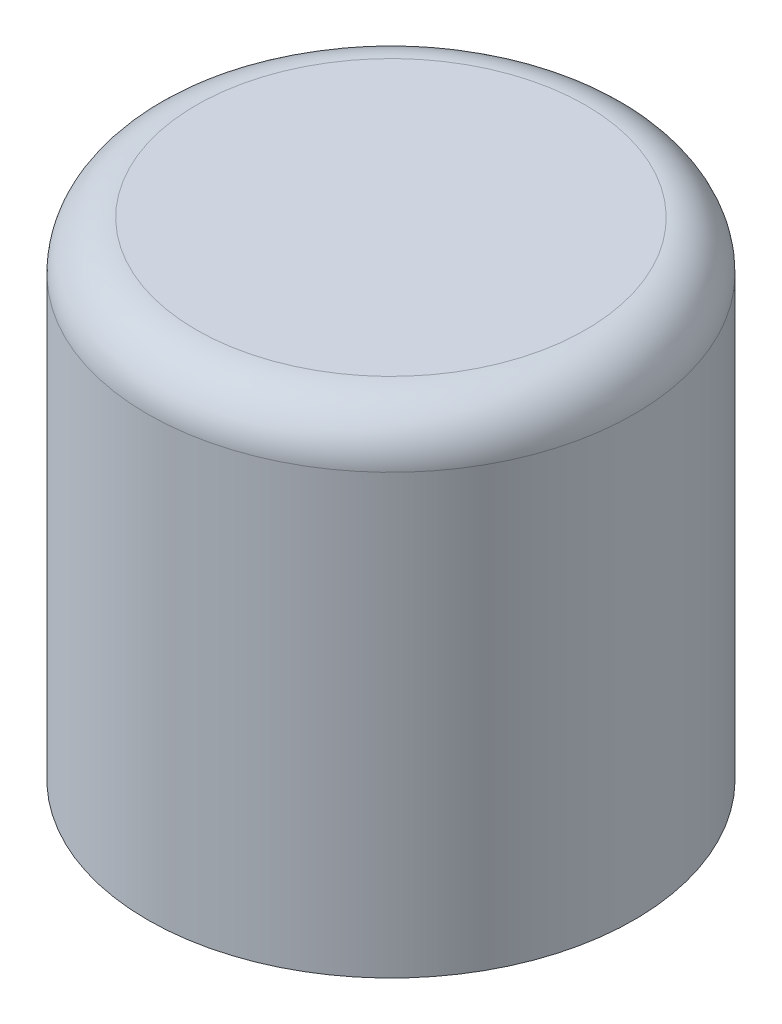
SolidWorks part; units mm, degrees
ref_plane "Front Plane" through (0, 0, 0) normal (0, 0, 1) x (1, 0, 0)
ref_plane "Top Plane" through (0, 0, 0) normal (0, 1, 0) x (1, 0, 0)
ref_plane "Right Plane" through (0, 0, 0) normal (1, 0, 0) x (0, 0, -1)
sketch "Sketch1" plane through (0, 0, 0) normal (0, 1, 0) x (1, 0, 0)
  circle A0 centre (0, 0) radius 5
extrude "Boss-Extrude1" add sketch "Sketch1" along normal blind 10
fillet "Fillet1" radius 1 1 edges at (0, 10, 5)
